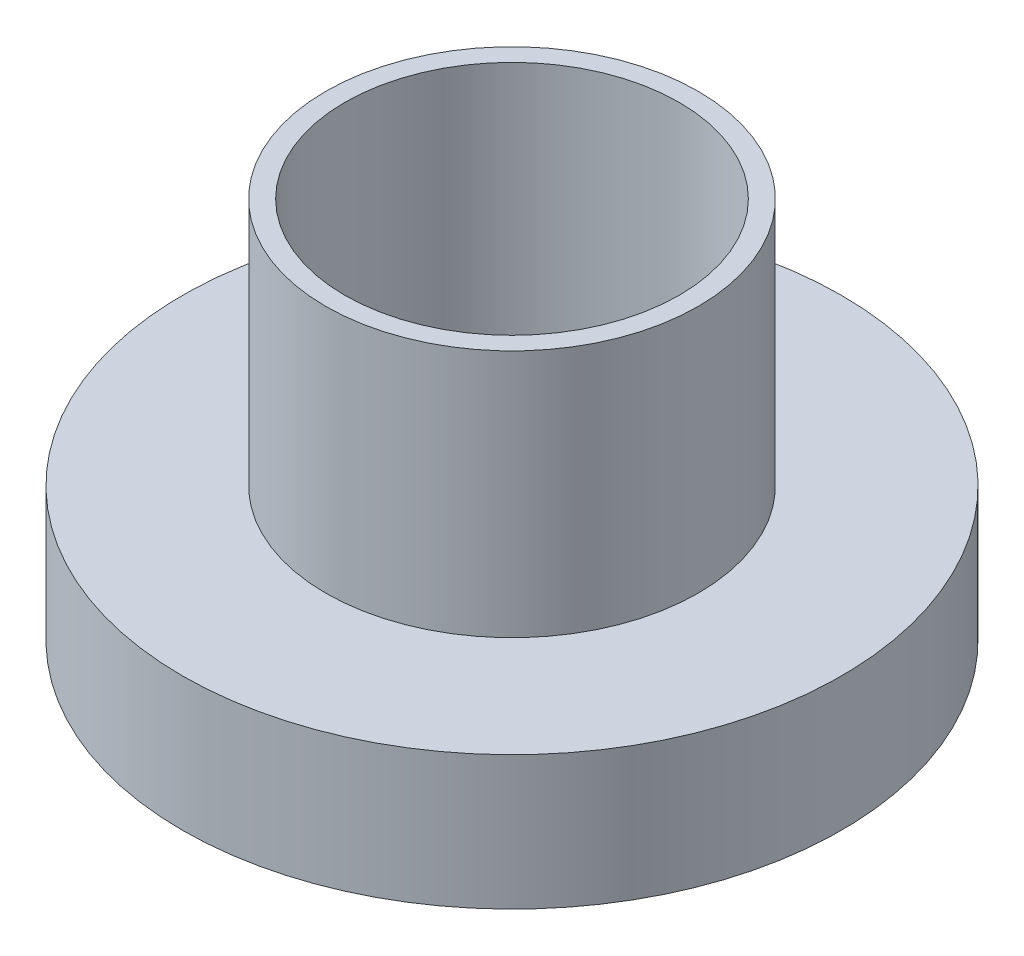
SolidWorks part; units mm, degrees
material "6061-T6 (SS)"
ref_plane "Front Plane" through (0, 0, 0) normal (0, 0, 1) x (1, 0, 0)
ref_plane "Top Plane" through (0, 0, 0) normal (0, 1, 0) x (1, 0, 0)
ref_plane "Right Plane" through (0, 0, 0) normal (1, 0, 0) x (0, 0, -1)
sketch "Sketch1" plane through (0, 0, 0) normal (0, 0, 1) x (1, 0, 0)
  line L0 (0, 0) -> (0, 40) construction
  line L4 (17.5, 40) -> (17.5, 9.815)
  line L5 (17.5, 9.815) -> (34.5, 0)
  line L7 (34.5, 0) -> (34.5, 14)
  line L10 (0, 0) -> (34.5, 0) construction
  line L11 (17.5, 40) -> (19.5, 40)
  line L12 (19.5, 40) -> (19.5, 14)
  line L13 (19.5, 14) -> (34.5, 14)
  point P5 (0, 0)
  point P6 (33.9139, 0.4142)
  dimension "D1" = 69
  dimension "D2" = 30
  dimension "D3" = 35
  dimension "D4" = 2
  dimension "D5" = 14
  dimension "D6" = 40
revolve "Revolve1" add sketch "Sketch1" angle 360 about L0
